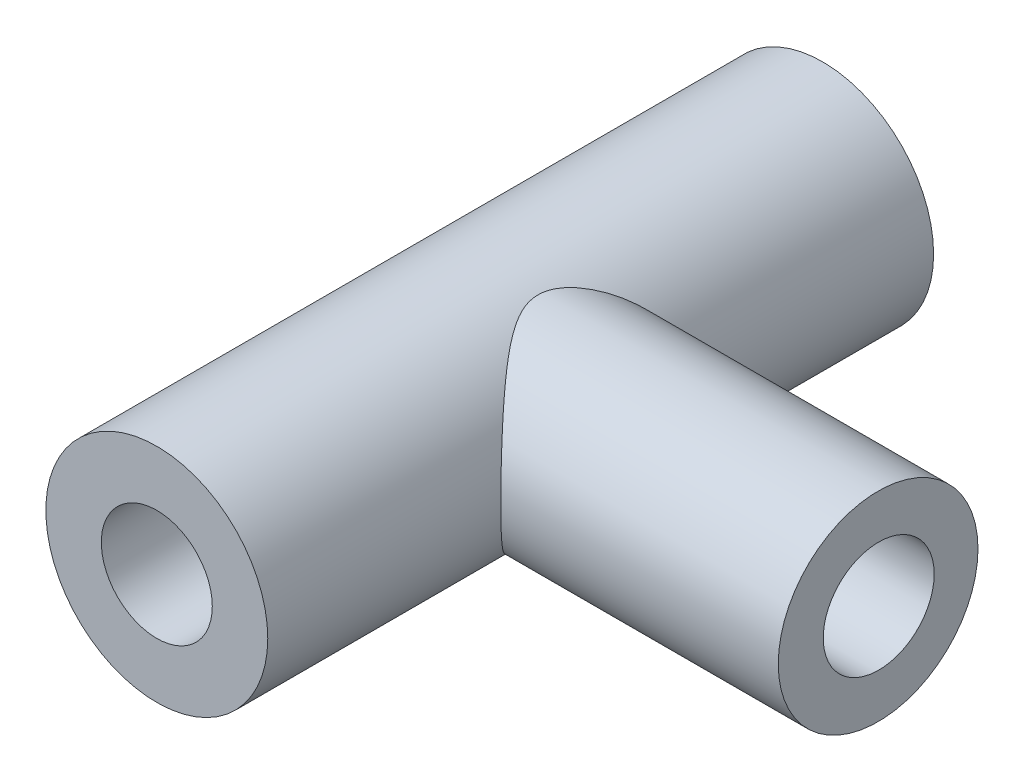
SolidWorks part; units mm, degrees
ref_plane "Front Plane" through (0, 0, 0) normal (0, 0, 1) x (1, 0, 0)
ref_plane "Top Plane" through (0, 0, 0) normal (0, 1, 0) x (1, 0, 0)
ref_plane "Right Plane" through (0, 0, 0) normal (1, 0, 0) x (0, 0, -1)
sketch "Sketch1" plane through (0, 0, 0) normal (0, 0, 1) x (1, 0, 0)
  circle A0 centre (0, 0) radius 10
  dimension "D1" = 20
extrude "Extrude-Thin1" add sketch "Sketch1" along normal blind 60 thin thin type one direction reverse wall 5
ref_plane "Plane1" through (35, 0, 0) normal (1, 0, 0) x (0, 0, -1)
sketch "Sketch2" plane through (35, 0, 0) normal (1, 0, 0) x (0, 0, -1)
  circle A0 centre (-30, 0) radius 9
  dimension "D2" = 18
  dimension "D1" = 30
extrude "Boss-Extrude2" add sketch "Sketch2" against normal up to next
sketch "Sketch3" plane through (35, 0, 0) normal (1, 0, 0) x (0, 0, -1)
  circle A0 centre (-29.9483, 0) radius 5
  dimension "D1" = 10
extrude "Cut-Extrude1" cut sketch "Sketch3" against normal up to next
